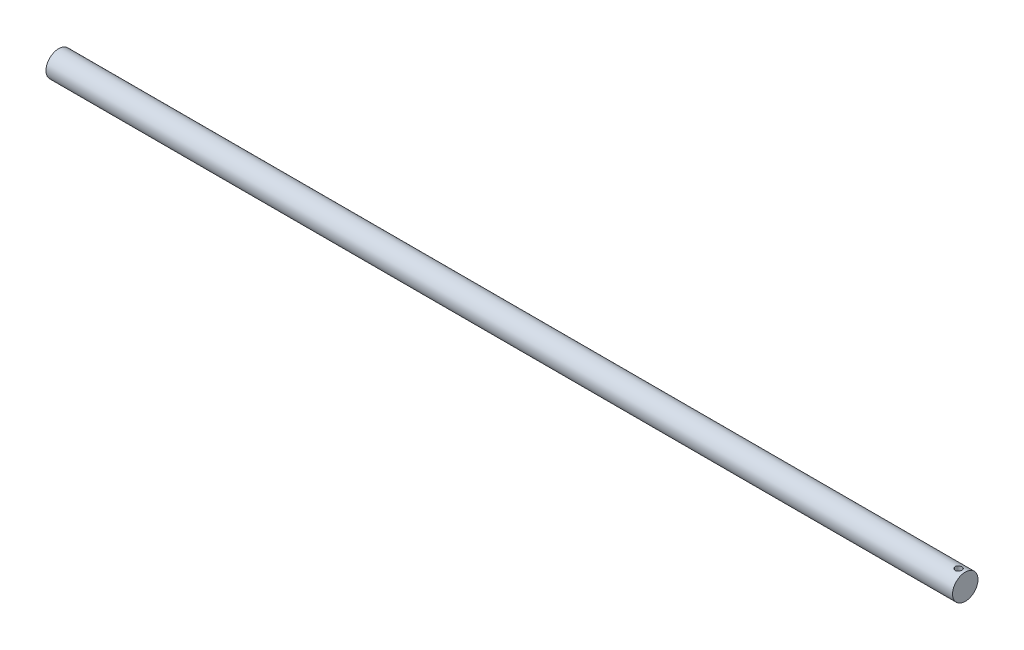
SolidWorks part; units mm, degrees
ref_plane "Front Plane" through (0, 0, 0) normal (0, 0, 1) x (1, 0, 0)
ref_plane "Top Plane" through (0, 0, 0) normal (0, 1, 0) x (1, 0, 0)
ref_plane "Right Plane" through (0, 0, 0) normal (1, 0, 0) x (0, 0, -1)
sketch "Sketch1" plane through (0, 0, 0) normal (1, 0, 0) x (0, 0, -1)
  circle A0 centre (0, 0) radius 4.85
  dimension "D1" = 9.7
extrude "Boss-Extrude1" add sketch "Sketch1" along normal blind 345.8672
sketch "Sketch2" plane through (0, 0, 0) normal (0, 1, 0) x (1, 0, 0)
  line L0 (345.8672, -4.85) -> (345.8672, 4.85) construction
  circle A0 centre (343.3672, 0) radius 1.25
  dimension "D1" = 2.5
  dimension "D2" = 2.5
extrude "Cut-Extrude1" cut sketch "Sketch2" against normal through all both and the other way through all
scale "Scale1" scale about centroid uniform scaling yes scale factor 1.5
